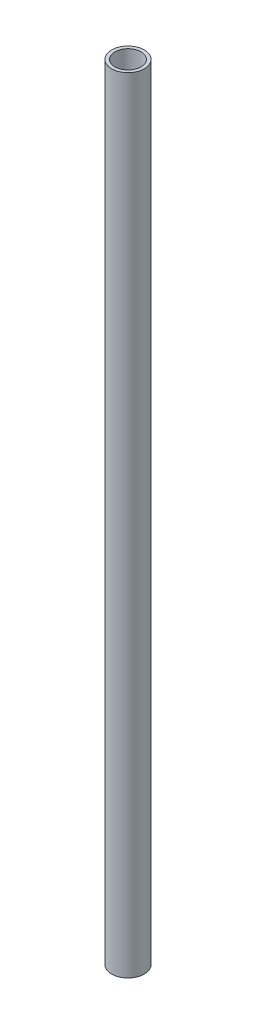
SolidWorks part; units mm, degrees
material "Hexcel AS4C (3000 丝)"
ref_plane "前视基准面" through (0, 0, 0) normal (0, 0, 1) x (1, 0, 0)
ref_plane "上视基准面" through (0, 0, 0) normal (0, 1, 0) x (1, 0, 0)
ref_plane "右视基准面" through (0, 0, 0) normal (1, 0, 0) x (0, 0, -1)
sketch "草图1" plane through (0, 0, 0) normal (0, 1, 0) x (1, 0, 0)
  circle A0 centre (0, 0) radius 10
  circle A1 centre (0, 0) radius 8
  dimension "D1" = 20
  dimension "D2" = 16
extrude "凸台-拉伸1" add sketch "草图1" along normal blind 480
